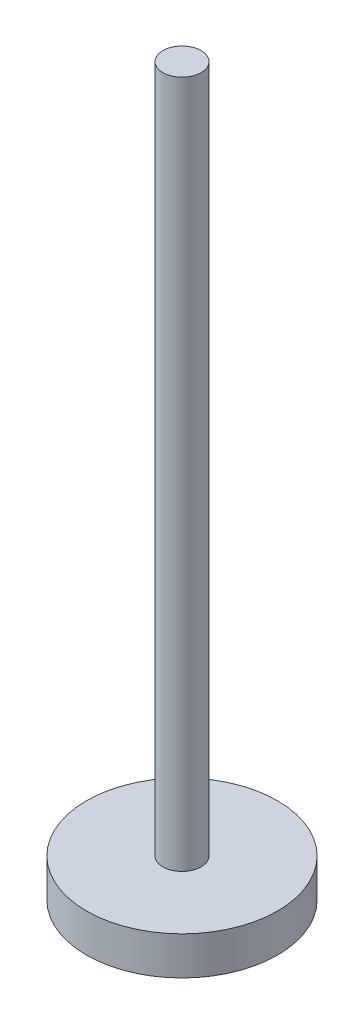
SolidWorks part; units mm, degrees
material "Aluminum"
ref_plane "Front Plane" through (0, 0, 0) normal (0, 0, 1) x (1, 0, 0)
ref_plane "Top Plane" through (0, 0, 0) normal (0, 1, 0) x (1, 0, 0)
ref_plane "Right Plane" through (0, 0, 0) normal (1, 0, 0) x (0, 0, -1)
sketch "Sketch1" plane through (0, 0, 0) normal (0, 0, 1) x (1, 0, 0)
  line L0 (1.5, 19) -> (1, 19)
  line L1 (1, 19) -> (1, 0)
  line L2 (1, 0) -> (3.5, 0)
  line L3 (3.5, 0) -> (3.5, 1)
  line L4 (3.5, 1) -> (1.5, 1)
  line L5 (1.5, 1) -> (1.5, 19)
  line L6 (1, 19) -> (1, 0) construction
  dimension "D1" = 1
  dimension "D2" = 2.5
  dimension "D3" = 2
  dimension "D4" = 19
revolve "Revolve1" add sketch "Sketch1" angle 360 about L6
